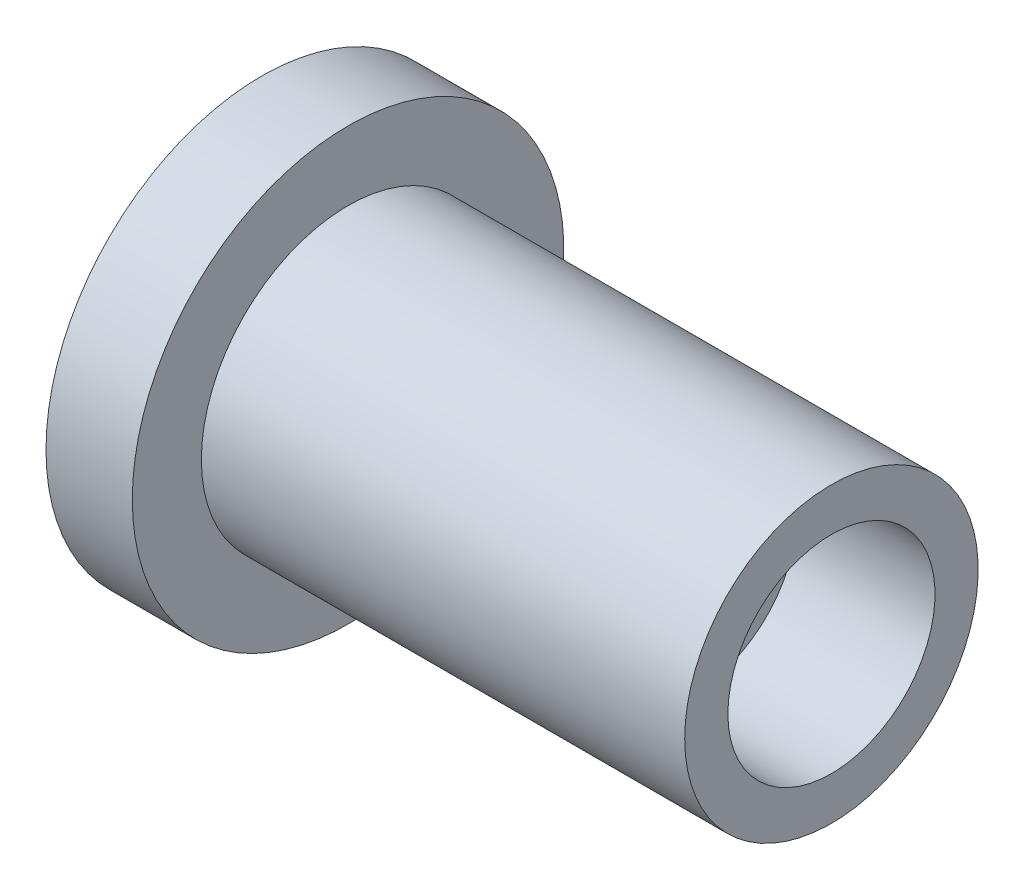
SolidWorks part; units mm, degrees
ref_plane "Спереди" through (0, 0, 0) normal (0, 0, 1) x (1, 0, 0)
ref_plane "Сверху" through (0, 0, 0) normal (0, 1, 0) x (1, 0, 0)
ref_plane "Справа" through (0, 0, 0) normal (1, 0, 0) x (0, 0, -1)
sketch "Эскиз1" plane through (0, 0, 0) normal (0, 0, 1) x (1, 0, 0)
  line L0 (0, 0) -> (40.4917, 0) construction
  line L1 (0, 0) -> (0, 6)
  line L2 (0, 6) -> (2, 6)
  line L3 (2, 6) -> (2, 12.5)
  line L4 (2, 12.5) -> (7, 12.5)
  line L5 (7, 12.5) -> (7, 8.5)
  line L6 (7, 8.5) -> (35, 8.5)
  line L7 (35, 8.5) -> (35, 6)
  line L8 (35, 6) -> (27, 6)
  line L9 (27, 6) -> (27, 0)
  line L10 (27, 0) -> (0, 0)
  dimension "D1" = 12
  dimension "D2" = 2
  dimension "D3" = 25
  dimension "D4" = 5
  dimension "D5" = 17
  dimension "D6" = 35
  dimension "D7" = 8
  dimension "D8" = 12
revolve "Повернуть1" add sketch "Эскиз1" angle 360 about L0
